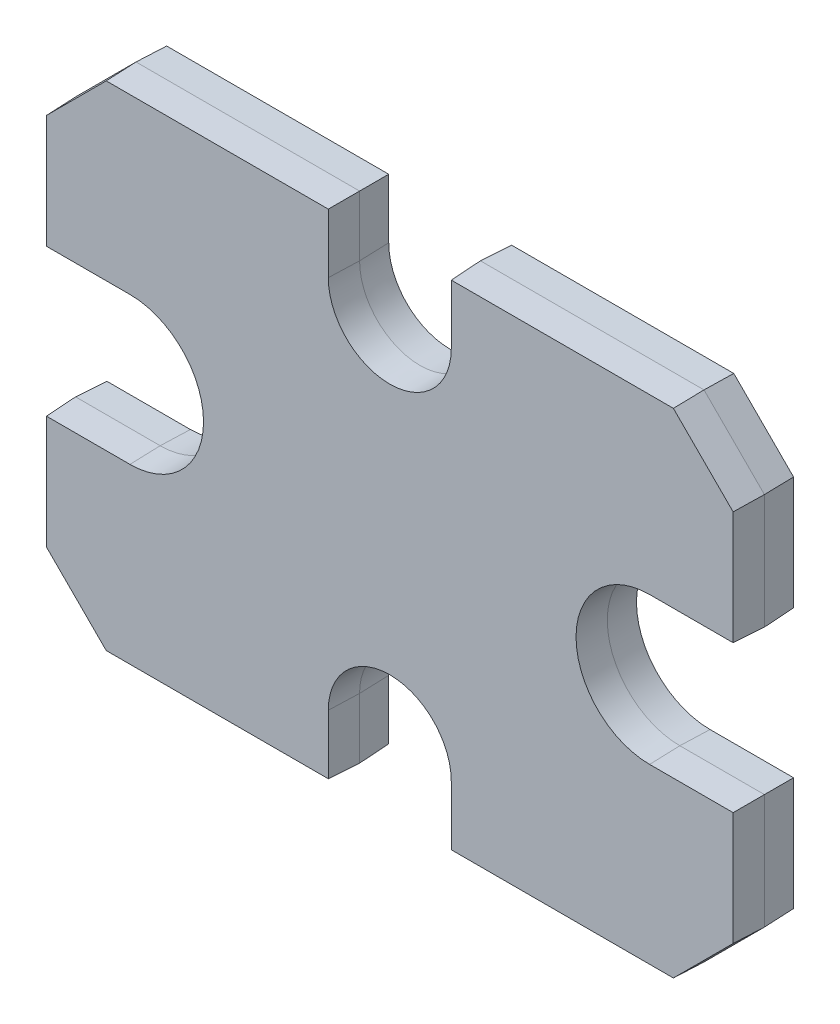
SolidWorks part; units mm, degrees
ref_plane "Front Plane" through (0, 0, 0) normal (0, 0, 1) x (1, 0, 0)
ref_plane "Top Plane" through (0, 0, 0) normal (0, 1, 0) x (1, 0, 0)
ref_plane "Right Plane" through (0, 0, 0) normal (1, 0, 0) x (0, 0, -1)
sketch "Sketch1" plane through (0, 0, 0) normal (0, 0, 1) x (1, 0, 0)
  line L0 (0, 0) -> (-50000, 0) construction
  line L1 (47, 41) -> (57, 31)
  line L2 (-47, 41) -> (-10, 41)
  line L3 (-57, 31) -> (-57, 12)
  line L4 (-47, -41) -> (-10, -41)
  line L5 (57, 31) -> (57, 12)
  line L6 (-57, 41) -> (57, -41) construction
  line L7 (-57, -41) -> (57, 41) construction
  line L8 (47, -41) -> (57, -31)
  line L9 (-57, -31) -> (-47, -41)
  line L10 (-57, 31) -> (-47, 41)
  line L11 (-10, 41) -> (-10, 31)
  line L12 (10, 31) -> (10, 41)
  line L13 (57, 12) -> (43, 12)
  line L14 (10, -31) -> (10, -41)
  line L15 (-10, -41) -> (-10, -31)
  line L16 (10, 41) -> (47, 41)
  line L17 (10, -41) -> (47, -41)
  line L18 (43, -12) -> (57, -12)
  line L19 (0, 14.4155) -> (0, -9.3634) construction
  line L20 (-43, -12) -> (-57, -12)
  line L21 (-57, 12) -> (-43, 12)
  line L22 (57, -12) -> (57, -31)
  line L23 (-57, -12) -> (-57, -31)
  arc A0 (-10, 31) -> (10, 31) centre (0, 31) ccw
  arc A1 (-10, -31) -> (10, -31) centre (0, -31) cw
  arc A2 (43, 12) -> (43, -12) centre (43, 0) ccw
  arc A3 (-43, 12) -> (-43, -12) centre (-43, 0) cw
  point P3 (0, 0)
  point P38 (10, 36)
  point P39 (0, 0)
  point P40 (50, 12)
  point P41 (0, 0)
  dimension "D3" = 10
  dimension "D4" = 12
  dimension "D11" = 20
  dimension "D12" = 10
  dimension "D1" = 114
  dimension "D2" = 82
  dimension "D9" = 20
  dimension "D10" = 19
  dimension "D13" = 14
  dimension "D14" = 62
extrude "Boss-Extrude1" add sketch "Sketch1" along normal mid plane 10 draft 2
